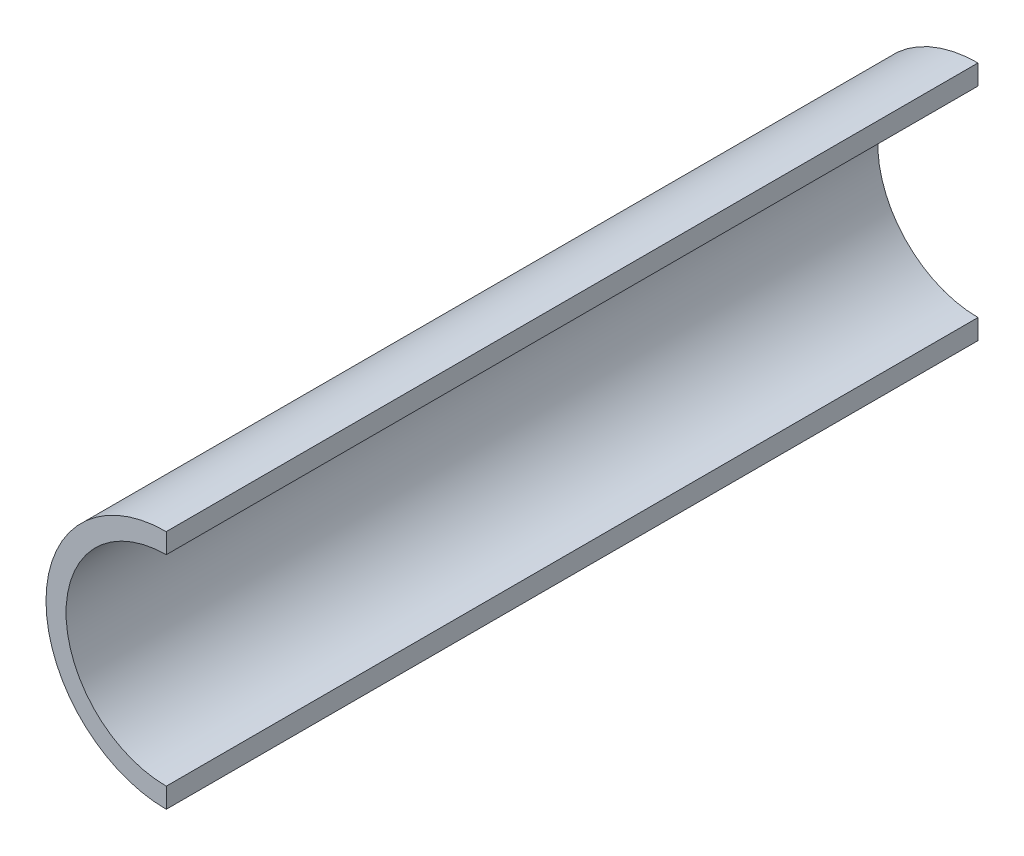
SolidWorks part; units mm, degrees
ref_plane "Front Plane" through (0, 0, 0) normal (0, 0, 1) x (1, 0, 0)
ref_plane "Top Plane" through (0, 0, 0) normal (0, 1, 0) x (1, 0, 0)
ref_plane "Right Plane" through (0, 0, 0) normal (1, 0, 0) x (0, 0, -1)
sketch "Sketch1" plane through (0, 0, 0) normal (0, 0, 1) x (1, 0, 0)
  line L0 (0, 9.525) -> (0, 7.9375)
  line L1 (0, -7.9375) -> (0, -9.525)
  arc A0 (0, 7.9375) -> (0, -7.9375) centre (0, 0) ccw
  arc A1 (0, 9.525) -> (0, -9.525) centre (0, 0) ccw
  dimension "D1" = 15.875
  dimension "D2" = 1.5875
extrude "Boss-Extrude1" add sketch "Sketch1" along normal blind 64.295
